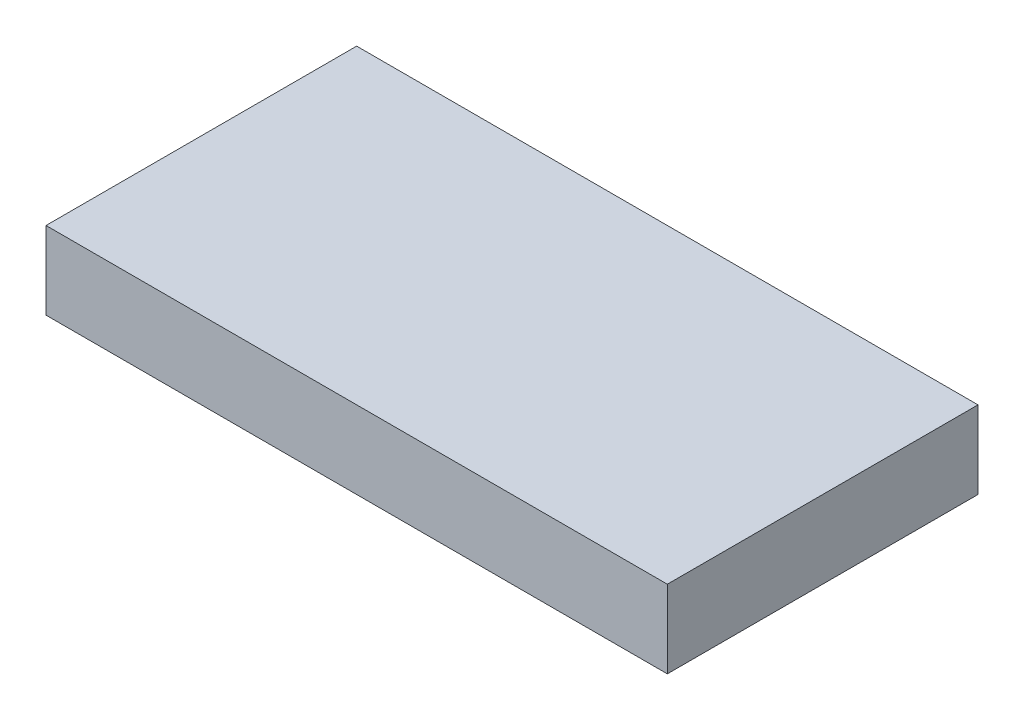
SolidWorks part; units mm, degrees
ref_plane "Front Plane" through (0, 0, 0) normal (0, 0, 1) x (1, 0, 0)
ref_plane "Top Plane" through (0, 0, 0) normal (0, 1, 0) x (1, 0, 0)
ref_plane "Right Plane" through (0, 0, 0) normal (1, 0, 0) x (0, 0, -1)
sketch "Sketch1" plane through (0, 0, 0) normal (0, 1, 0) x (1, 0, 0)
  line L1 (-39.7747, -12.4907) -> (11.0253, -12.4907)
  line L2 (-39.7747, -12.4907) -> (-39.7747, 12.9093)
  line L3 (-39.7747, 12.9093) -> (11.0253, 12.9093)
  line L4 (11.0253, -12.4907) -> (11.0253, 12.9093)
  dimension "D1" = 25.4
  dimension "D2" = 50.8
extrude "Boss-Extrude1" add sketch "Sketch1" along normal blind 6.35
